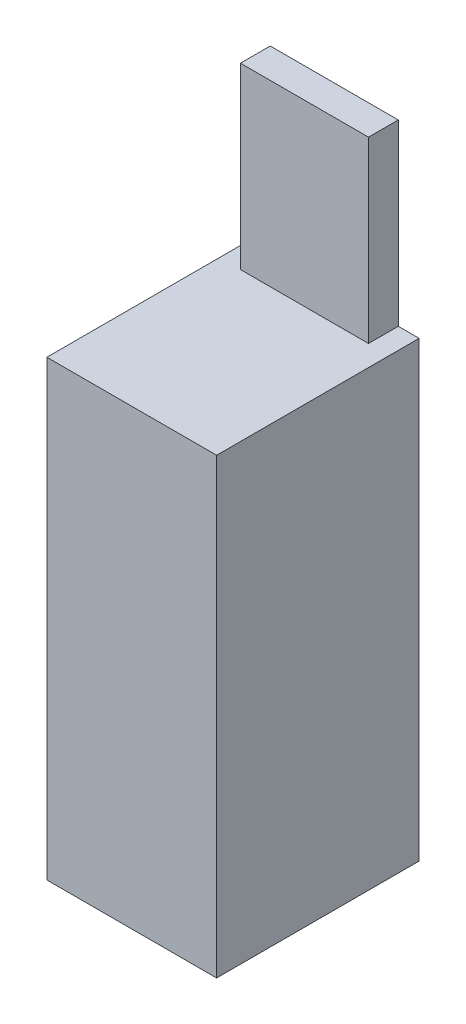
SolidWorks part; units mm, degrees
ref_plane "Front Plane" through (0, 0, 0) normal (0, 0, 1) x (1, 0, 0)
ref_plane "Top Plane" through (0, 0, 0) normal (0, 1, 0) x (1, 0, 0)
ref_plane "Right Plane" through (0, 0, 0) normal (1, 0, 0) x (0, 0, -1)
sketch "Sketch1" plane through (0, 0, 0) normal (0, 1, 0) x (1, 0, 0)
  line L1 (0, 0) -> (28.5, 0)
  line L2 (0, 0) -> (0, 34)
  line L3 (0, 34) -> (28.5, 34)
  line L4 (28.5, 0) -> (28.5, 34)
  dimension "D1" = 28.5
  dimension "D2" = 34
extrude "Boss-Extrude1" add sketch "Sketch1" along normal blind 76
sketch "Sketch2" plane through (0, 76, 0) normal (0, 1, 0) x (1, 0, 0)
  line L0 (14.25, 34) -> (14.25, 0) construction
  line L1 (28.5, 34) -> (0, 34) construction
  line L2 (0, 0) -> (28.5, 0) construction
  line L4 (3.5, 29) -> (25, 29)
  line L5 (3.5, 29) -> (3.5, 34)
  line L6 (3.5, 34) -> (25, 34)
  line L7 (25, 29) -> (25, 34)
  line L8 (3.5, 29) -> (25, 34) construction
  line L9 (3.5, 34) -> (25, 29) construction
  point P6 (14.25, 31.5)
  dimension "D1" = 21.5
  dimension "D2" = 5
extrude "Boss-Extrude2" add sketch "Sketch2" along normal blind 30
